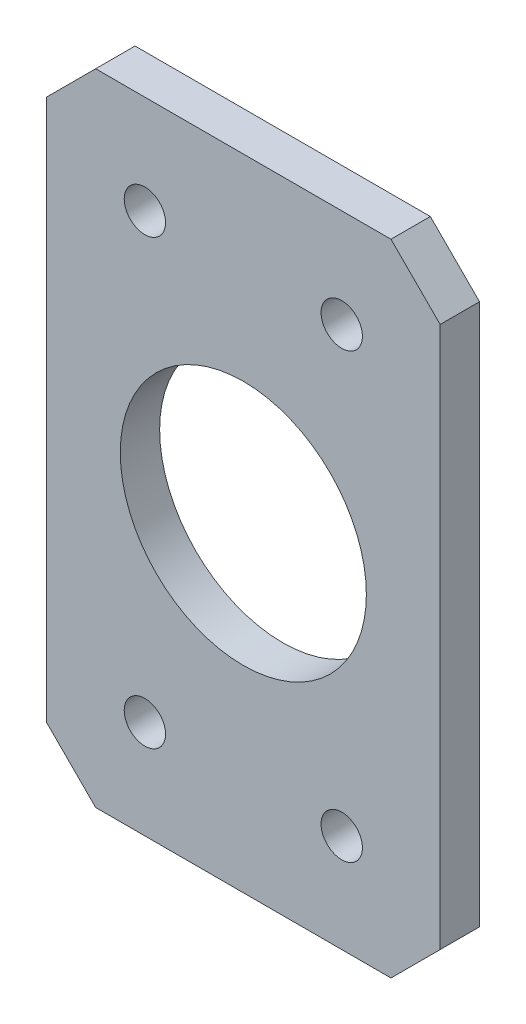
SolidWorks part; units mm, degrees
ref_plane "前视基准面" through (0, 0, 0) normal (0, 0, 1) x (1, 0, 0)
ref_plane "上视基准面" through (0, 0, 0) normal (0, 1, 0) x (1, 0, 0)
ref_plane "右视基准面" through (0, 0, 0) normal (1, 0, 0) x (0, 0, -1)
sketch "草图1" plane through (0, 0, 0) normal (0, 0, 1) x (1, 0, 0)
  line L1 (20, -32.5) -> (-20, -32.5)
  line L2 (20, -32.5) -> (20, 32.5)
  line L3 (20, 32.5) -> (-20, 32.5)
  line L4 (-20, -32.5) -> (-20, 32.5)
  line L5 (20, -32.5) -> (-20, 32.5) construction
  line L6 (20, 32.5) -> (-20, -32.5) construction
  circle A0 centre (0, 0) radius 12.5
  dimension "D1" = 25
  dimension "D2" = 65
  dimension "D3" = 40
extrude "凸台-拉伸1" add sketch "草图1" along normal mid plane 4
sketch "草图2" plane through (0, 0, -2) normal (0, 0, -1) x (-1, 0, 0)
  line L0 (-20, 32.5) -> (20, 32.5) construction
  line L1 (10, -22.5) -> (-10, -22.5) construction
  line L2 (10, -22.5) -> (10, 22.5) construction
  line L3 (10, 22.5) -> (-10, 22.5) construction
  line L4 (-10, -22.5) -> (-10, 22.5) construction
  line L5 (10, -22.5) -> (-10, 22.5) construction
  line L6 (10, 22.5) -> (-10, -22.5) construction
  line L7 (-20, -32.5) -> (-20, 32.5) construction
  circle A0 centre (-10, 22.5) radius 2.1
  circle A1 centre (10, 22.5) radius 2.1
  circle A2 centre (10, -22.5) radius 2.1
  circle A3 centre (-10, -22.5) radius 2.1
  point P0 (0, 0)
  dimension "D1" = 10
  dimension "D3" = 4.2
  dimension "D2" = 10
extrude "切除-拉伸1" cut sketch "草图2" against normal through all both and the other way through all
chamfer "倒角2" distance 5 angle 45 4 edges at (20, 32.5, 0) (20, -32.5, 0) (-20, -32.5, 0) (-20, 32.5, 0)
